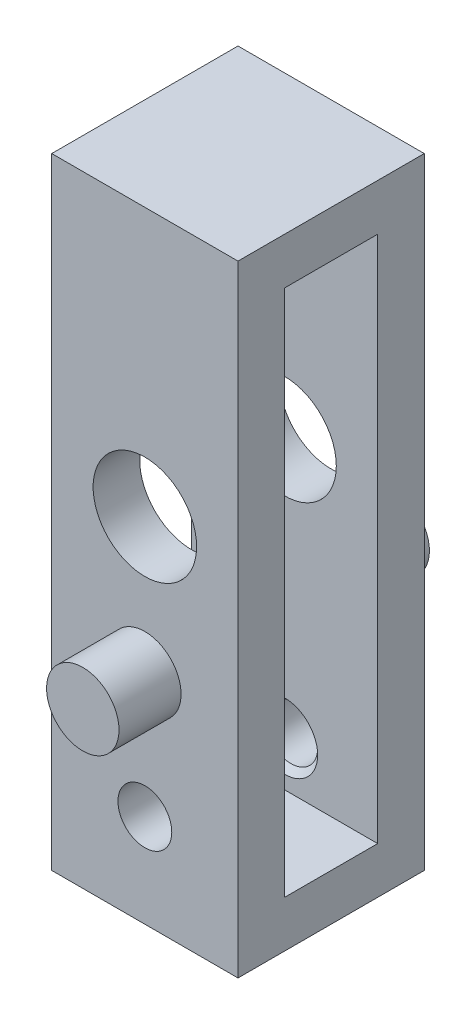
SolidWorks part; units mm, degrees
ref_plane "Front Plane" through (0, 0, 0) normal (0, 0, 1) x (1, 0, 0)
ref_plane "Top Plane" through (0, 0, 0) normal (0, 1, 0) x (1, 0, 0)
ref_plane "Right Plane" through (0, 0, 0) normal (1, 0, 0) x (0, 0, -1)
sketch "Sketch2" plane through (0, 0, 0) normal (0, 1, 0) x (1, 0, 0)
  line L1 (-45, -45) -> (45, -45)
  line L2 (-45, -45) -> (-45, 45)
  line L3 (-45, 45) -> (45, 45)
  line L4 (45, -45) -> (45, 45)
  line L5 (-45, -45) -> (45, 45) construction
  line L6 (-45, 45) -> (45, -45) construction
  point P0 (0, 0)
  dimension "D1" = 90
  dimension "D2" = 90
extrude "Boss-Extrude1" add sketch "Sketch2" along normal blind 300
sketch "Sketch3" plane through (45, 0, 0) normal (1, 0, 0) x (0, 0, -1)
  line L0 (-22.5, 22.5) -> (22.5, 22.5)
  line L1 (22.5, 22.5) -> (22.5, 277.5)
  line L2 (22.5, 277.5) -> (-22.5, 277.5)
  line L3 (-22.5, 277.5) -> (-22.5, 22.5)
  line L4 (-45, 0) -> (45, 0)
  line L5 (45, 0) -> (45, 300)
  line L6 (45, 300) -> (-45, 300)
  line L7 (-45, 300) -> (-45, 0)
  line L8 (-45, 0) -> (45, 0)
  line L9 (45, 0) -> (45, 300)
  line L10 (45, 300) -> (-45, 300)
  line L11 (-45, 300) -> (-45, 0)
  dimension "D2" = 45
  dimension "D1" = 0
extrude "Cut-Extrude1" cut sketch "Sketch3" against normal through all contours L0 L1 L2 L3
sketch "Sketch4" plane through (0, 0, 45) normal (0, 0, 1) x (1, 0, 0)
  circle A0 centre (0, 170.5) radius 25
  dimension "D1" = 50
  dimension "D2" = 148
extrude "Crank shaft hole" cut sketch "Sketch4" against normal blind 90
sketch "Sketch5" plane through (0, 0, 45) normal (0, 0, 1) x (1, 0, 0)
  circle A0 centre (0, 45) radius 13
  dimension "D1" = 26
  dimension "D2" = 22.5
extrude "Cut-Extrude3" cut sketch "Sketch5" against normal blind 90
chamfer "Chamfer1" distance 3 angle 45 2 edges at (13, 45, 22.5) (-13, 45, -22.5)
sketch "Sketch6" plane through (0, 0, 45) normal (0, 0, 1) x (1, 0, 0)
  circle A0 centre (0, 105) radius 17.5
  circle A1 centre (0, 45) radius 13 construction
  dimension "D1" = 35
  dimension "D2" = 60
extrude "Boss-Extrude2" add sketch "Sketch6" along normal blind 30
mirror "Mirror1" about plane through (0, 0, 0) normal (0, 0, 1) of "Boss-Extrude2"
